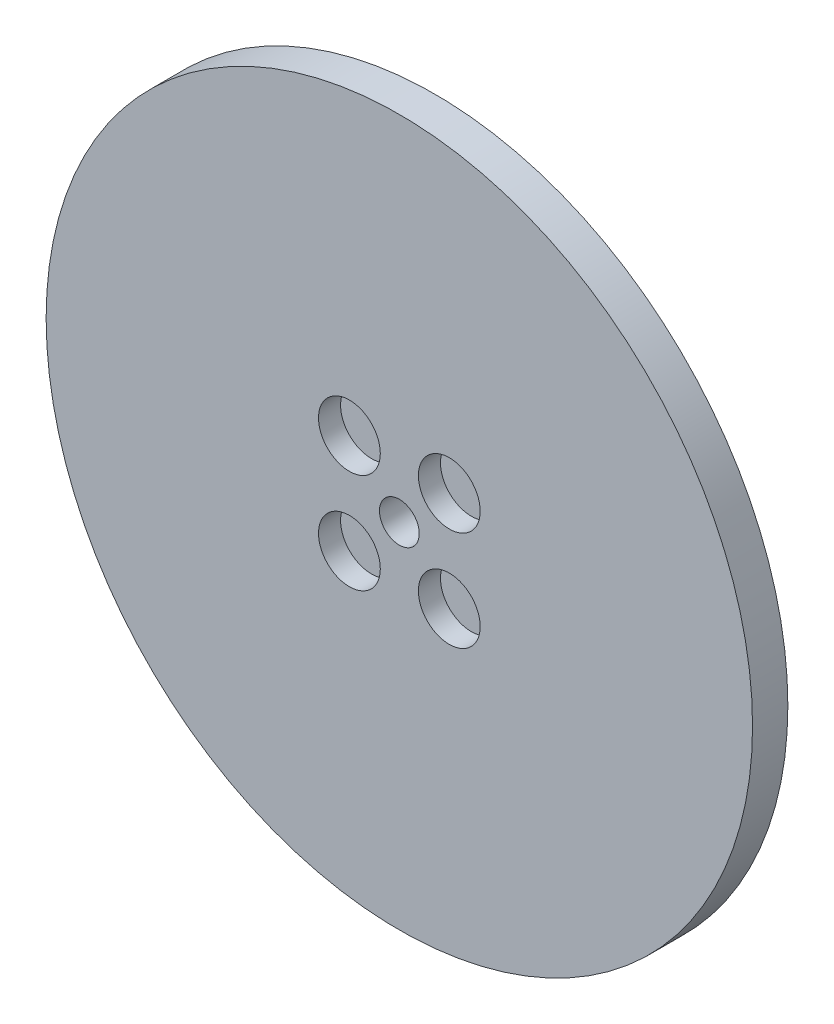
SolidWorks part; units mm, degrees
ref_plane "Front Plane" through (0, 0, 0) normal (0, 0, 1) x (1, 0, 0)
ref_plane "Top Plane" through (0, 0, 0) normal (0, 1, 0) x (1, 0, 0)
ref_plane "Right Plane" through (0, 0, 0) normal (1, 0, 0) x (0, 0, -1)
sketch "Sketch1" plane through (0, 0, 0) normal (0, 0, 1) x (1, 0, 0)
  circle A0 centre (0, 0) radius 12.5
  circle A1 centre (0, 0) radius 30
  dimension "D1" = 25
  dimension "D2" = 60
extrude "Boss-Extrude1" add sketch "Sketch1" along normal blind 4
sketch "Sketch2" plane through (0, 0, 4) normal (0, 0, 1) x (1, 0, 0)
  line L1 (-5.656, 5.6577) -> (5.656, 5.6577) construction
  line L2 (-5.656, 5.6577) -> (-5.656, -5.6577) construction
  line L3 (-5.656, -5.6577) -> (5.656, -5.6577) construction
  line L4 (5.656, 5.6577) -> (5.656, -5.6577) construction
  circle A0 centre (0, 0) radius 2.25
  circle A1 centre (-5.656, 5.6577) radius 1.5
  circle A2 centre (-5.656, -5.6577) radius 1.5
  circle A3 centre (5.656, -5.6577) radius 1.5
  circle A4 centre (5.656, 5.6577) radius 1.5
  circle A5 centre (0, 0) radius 40
  point P15 (0, -5.6577)
  point P16 (-5.656, 0)
  dimension "D1" = 4.5
  dimension "D4" = 3
  dimension "D5" = 80
  dimension "D2" = 16
  dimension "D3" = 11.3154
extrude "Boss-Extrude2" add sketch "Sketch2" along normal blind 4
sketch "Sketch3" plane through (0, 0, 8) normal (0, 0, 1) x (1, 0, 0)
  circle A0 centre (-5.656, 5.6577) radius 3.5
  circle A1 centre (5.656, 5.6577) radius 3.5
  circle A2 centre (5.656, -5.6577) radius 3.5
  circle A3 centre (-5.656, -5.6577) radius 3.5
  dimension "D1" = 7
extrude "Cut-Extrude1" cut sketch "Sketch3" against normal blind 2.5
sketch "Sketch4" plane through (0, 0, 0) normal (0, 0, -1) x (-1, 0, 0)
  circle A0 centre (-20, 0) radius 5.15
  circle A1 centre (0, -20) radius 5.15
  circle A2 centre (0, 0) radius 20 construction
  circle A3 centre (0, 0) radius 20 construction
  circle A4 centre (20, 0) radius 5.15
  circle A5 centre (0, 0) radius 20 construction
  circle A6 centre (0, 20) radius 5.15
  circle A7 centre (0, 0) radius 20 construction
  circle A8 centre (0, 20) radius 2.65 construction
  circle A9 centre (14.1421, 14.1421) radius 2.65
  circle A10 centre (0, 0) radius 20 construction
  circle A11 centre (20, 0) radius 2.65 construction
  circle A12 centre (0, 0) radius 20 construction
  circle A13 centre (14.1421, -14.1421) radius 2.65
  circle A14 centre (0, 0) radius 20 construction
  circle A15 centre (0, -20) radius 2.65 construction
  circle A16 centre (0, 0) radius 20 construction
  circle A17 centre (-14.1421, -14.1421) radius 2.65
  circle A18 centre (0, 0) radius 20 construction
  circle A19 centre (-20, 0) radius 2.65 construction
  circle A20 centre (0, 0) radius 20 construction
  circle A21 centre (-14.1421, 14.1421) radius 2.65
  circle A22 centre (0, 0) radius 20 construction
  point P17 (0, 0)
  point P39 (0, 0)
  dimension "D1" = 10.3
  dimension "D2" = 40
  dimension "D4" = 5.3
  dimension "D3" = 4
  dimension "D5" = 8
extrude "Cut-Extrude2" cut sketch "Sketch4" against normal blind 3
sketch "Sketch5" plane through (0, 0, 5.5) normal (0, 0, 1) x (1, 0, 0)
  circle A0 centre (-5.656, 5.6577) radius 3.5
  circle A1 centre (5.656, 5.6577) radius 3.5
  circle A2 centre (-5.656, -5.6577) radius 3.5
  circle A3 centre (5.656, -5.6577) radius 3.5
extrude "Boss-Extrude3" add sketch "Sketch5" against normal blind 0.2
